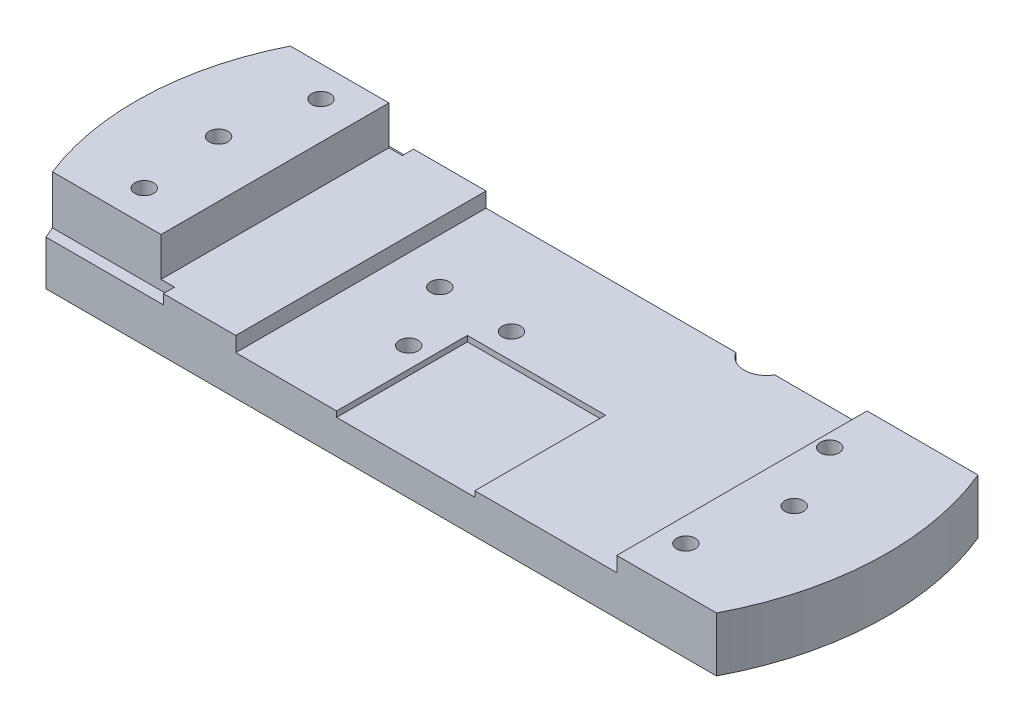
SolidWorks part; units mm, degrees
ref_plane "Front Plane" through (0, 0, 0) normal (0, 0, 1) x (1, 0, 0)
ref_plane "Top Plane" through (0, 0, 0) normal (0, 1, 0) x (1, 0, 0)
ref_plane "Right Plane" through (0, 0, 0) normal (1, 0, 0) x (0, 0, -1)
sketch "Sketch1" plane through (0, 0, 0) normal (0, 1, 0) x (1, 0, 0)
  line L1 (-97.5, -33.5) -> (97.5, -33.5)
  line L2 (-97.5, -33.5) -> (-97.5, 33.5)
  line L3 (-97.5, 33.5) -> (97.5, 33.5)
  line L4 (97.5, -33.5) -> (97.5, 33.5)
  line L5 (-97.5, -33.5) -> (97.5, 33.5) construction
  line L6 (-97.5, 33.5) -> (97.5, -33.5) construction
  point P0 (0, 0)
  dimension "D1" = 67
  dimension "D2" = 195
extrude "Boss-Extrude1" add sketch "Sketch1" along normal blind 25
sketch "Sketch2" plane through (0, 0, 0) normal (0, -1, 0) x (1, 0, 0)
  line L0 (-97.5, -33.5) -> (-97.5, 33.5) construction
  line L1 (97.5, 33.5) -> (97.5, -33.5) construction
  line L2 (97.5, 33.5) -> (88.5, 33.5)
  line L3 (-97.5, 33.5) -> (97.5, 33.5) construction
  line L4 (97.5, -33.5) -> (91.5, -33.5)
  line L5 (97.5, -33.5) -> (-97.5, -33.5) construction
  line L6 (-97.5, 33.5) -> (-91, 33.5)
  line L7 (-97.5, -33.5) -> (-88, -33.5)
  circle A0 centre (18.0922, -3.2198) radius 79.4078
  circle A1 centre (-22.6589, 2.9929) radius 74.8411
  line M7 (97.5, -33.5) -> (97.5, 33.5)
  line M8 (97.5, 33.5) -> (-97.5, 33.5)
  line M9 (-97.5, 33.5) -> (-97.5, -33.5)
  line M10 (-97.5, -33.5) -> (97.5, -33.5)
  dimension "D1" = 9
  dimension "D2" = 6
  dimension "D3" = 6.5
  dimension "D4" = 9.5
extrude "Cut-Extrude1" cut sketch "Sketch2" against normal through all contours A0 M7 M8 | A0 M10 M7 | A1 M9 M10 | A1 M8 M9
sketch "Sketch3" plane through (0, 0, 33.5) normal (0, 0, -1) x (-1, 0, 0)
  line L0 (97.5, 25) -> (63.2, 25)
  line L2 (63.2, 25) -> (63.2, 14.6)
  line L3 (63.2, 14.6) -> (40.2, 14.6)
  line L4 (40.2, 14.6) -> (40.2, 10.6)
  line L5 (40.2, 10.6) -> (-61.8, 10.6)
  line L6 (-91.5, 25) -> (88, 25) construction
  line L10 (97.5, 0) -> (97.5, 25) construction
  line L11 (-61.8, 10.6) -> (-61.8, 14.6)
  line L12 (-61.8, 14.6) -> (-97.5, 14.6)
  line L13 (-97.5, 25) -> (-97.5, 0) construction
  line L14 (-97.5, 14.6) -> (-97.5, 25)
  line L15 (-97.5, 25) -> (63.2, 25)
  line M13 (-88.5, 0) -> (-88.5, 25)
  line M14 (-88.5, 25) -> (91, 25)
  dimension "D1" = 10.4
  dimension "D2" = 34.3
  dimension "D3" = 23
  dimension "D4" = 4
  dimension "D5" = 102
extrude "Cut-Extrude2" cut sketch "Sketch3" along normal through all contours L11 L12 L2 L3 L4 L5 M13 M14
sketch "Sketch4" plane through (0, 25, 0) normal (0, 1, 0) x (1, 0, 0)
  line L0 (-59.5873, 33.5) -> (-59.5873, 30.5)
  line L1 (-63.2, 33.5) -> (-88, 33.5) construction
  line L2 (-59.5873, 30.5) -> (-89.5873, 30.5)
  line L3 (-59.5873, -33.5) -> (-59.5873, -30.5)
  line L4 (-91, -33.5) -> (-63.2, -33.5) construction
  line L5 (-59.5873, -30.5) -> (-92.2617, -30.5)
  line L6 (-59.5873, 33.5) -> (-63.2, 33.5)
  line L7 (-59.5873, -33.5) -> (-63.2, -33.5)
  arc A0 (-88, 33.5) -> (-91, -33.5) centre (-22.6589, -2.9929) ccw construction
  line M5 (-91, -33.5) -> (-63.2, -33.5)
  line M6 (-63.2, -33.5) -> (-63.2, 33.5)
  line M7 (-63.2, 33.5) -> (-88, 33.5)
  arc M8 (-88, 33.5) -> (-91, -33.5) centre (-22.6589, -2.9929) ccw
  dimension "D1" = 3
  dimension "D2" = 3
  dimension "D3" = 30
extrude "Cut-Extrude3" cut sketch "Sketch4" against normal blind 13 contours L2 M6 M7 M8 | L0 L6 L2 M6 | L5 M6 M8 M5 | L7 L3 L5 M6
sketch "Sketch6" plane through (0, 0, 0) normal (0, -1, 0) x (1, 0, 0)
  line L0 (-63.2, -33.5) -> (-97.5, -33.5)
  line L1 (91.5, -33.5) -> (-88, -33.5) construction
  line L2 (-63.2, -33.5) -> (-63.2, 33.5)
  line L3 (-91, 33.5) -> (88.5, 33.5) construction
  line L4 (-63.2, -9) -> (-28.1, -9) construction
  line L5 (-63.2, 8.7) -> (-18.7, 8.7) construction
  line L6 (-63.2, -8.3) -> (-8.2, -8.3) construction
  line L8 (91.5, -33.5) -> (-88, -33.5) construction
  line L9 (-97.5, -33.5) -> (-97.5, 33.5)
  line L10 (-97.5, 33.5) -> (-63.2, 33.5)
  circle A0 centre (-28.1, -9) radius 2.5
  circle A1 centre (-18.7, 8.7) radius 2.5
  circle A2 centre (74.1, -1.7) radius 2.5
  circle A3 centre (68.3, 21.5) radius 2.5
  circle A4 centre (65.3, -20) radius 2.5
  circle A5 centre (-8.2, -8.3) radius 2.5
  circle A6 centre (-76.2, 22) radius 2.5
  circle A7 centre (-78.2, 0.1) radius 2.5
  circle A8 centre (-73.2, -22.3) radius 2.5
  arc A10 (-91, 33.5) -> (-88, -33.5) centre (-22.6589, 2.9929) ccw construction
  dimension "D2" = 5
  dimension "D3" = 35.1
  dimension "D4" = 34.3
  dimension "D5" = 44.5
  dimension "D6" = 24.5
  dimension "D7" = 55
  dimension "D8" = 42.2
  dimension "D9" = 137.3
  dimension "D10" = 128.5
  dimension "D11" = 131.5
  dimension "D12" = 10
  dimension "D13" = 15
  dimension "D14" = 13
  dimension "D15" = 11.2
  dimension "D16" = 33.6
  dimension "D17" = 55.5
  dimension "D18" = 31.8
  dimension "D19" = 55
  dimension "D20" = 13.5
  dimension "D21" = 25.2
extrude "Cut-Extrude4" cut sketch "Sketch6" against normal through all contours A0 | A5 | A1 | A6 | A7 | A8 | A4 | A2 | A3
sketch "Sketch7" plane through (0, 10.6, 0) normal (0, 1, 0) x (1, 0, 0)
  line L1 (-13.2, 1.5) -> (23.8, 1.5)
  line L2 (-13.2, 1.5) -> (-13.2, -33.5)
  line L3 (-13.2, -33.5) -> (23.8, -33.5)
  line L4 (23.8, 1.5) -> (23.8, -33.5)
  line L8 (-63.2, 30.5) -> (-63.2, -30.5) construction
  line L9 (-63.2, 30.5) -> (-63.2, -30.5) construction
  line L10 (-40.2, -33.5) -> (61.8, -33.5) construction
  dimension "D1" = 50
  dimension "D2" = 87
  dimension "D3" = 35
extrude "Cut-Extrude5" cut sketch "Sketch7" against normal blind 1.5
sketch "Sketch8" plane through (0, 25, 0) normal (0, 1, 0) x (1, 0, 0)
  line L0 (-59.5873, -33.5) -> (-97.5, -33.5)
  line L1 (-97.5, -33.5) -> (-97.5, 33.5)
  line L3 (-97.5, 33.5) -> (31.9, 33.5)
  line L6 (31.9, 36.5) -> (31.9, 30.5)
  line L7 (31.9, 33.5) -> (37.0962, 33.5)
  line L10 (-59.5873, 33.5) -> (-88, 33.5) construction
  line L11 (-40.2, 33.5) -> (61.8, 33.5) construction
  circle A1 centre (31.9, 36.5) radius 6
  arc A2 (-89.5873, 30.5) -> (-92.2617, -30.5) centre (-22.6589, -2.9929) ccw construction
  dimension "D1" = 12
  dimension "D2" = 129.4
extrude "Cut-Extrude6" cut sketch "Sketch8" against normal blind 18.5 contours L6 A1 L7 | L3 A1 L6
